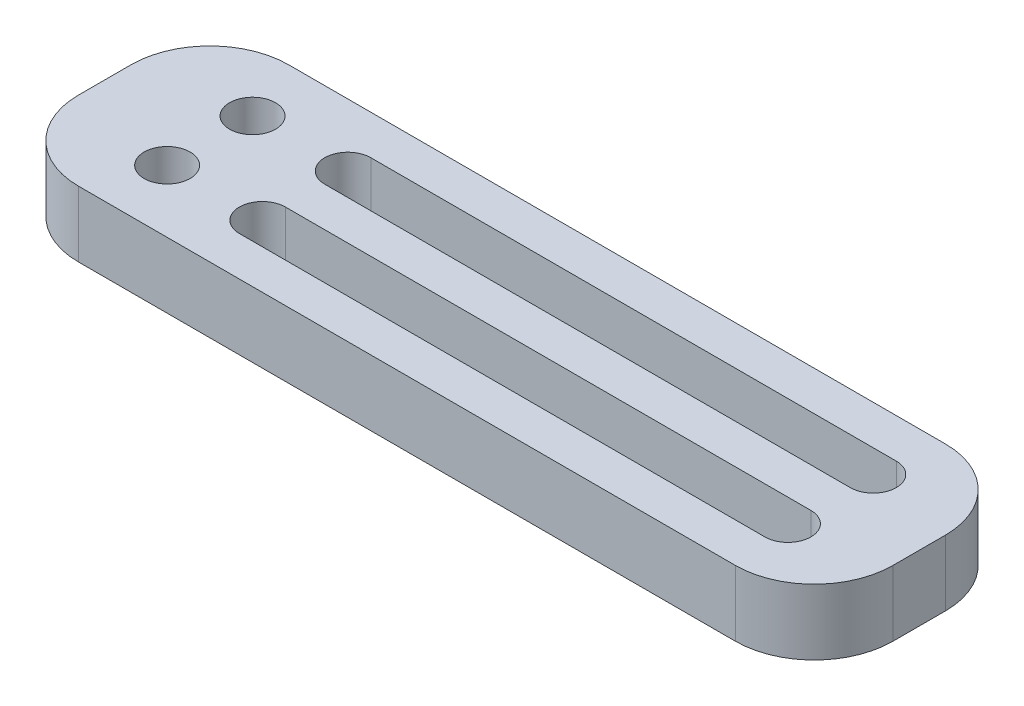
SolidWorks part; units mm, degrees
ref_plane "Front Plane" through (0, 0, 0) normal (0, 0, 1) x (1, 0, 0)
ref_plane "Top Plane" through (0, 0, 0) normal (0, 1, 0) x (1, 0, 0)
ref_plane "Right Plane" through (0, 0, 0) normal (1, 0, 0) x (0, 0, -1)
sketch "Sketch1" plane through (0, 0, 0) normal (0, 1, 0) x (1, 0, 0)
  line L0 (8, -10) -> (8, 6) construction
  line L1 (6, 6) -> (56, 6)
  line L2 (0, 0) -> (0, -4)
  line L3 (15.25, 1.25) -> (8, 1.25) construction
  line L4 (62, 0) -> (62, -4)
  line L5 (62, -2) -> (0, -2) construction
  line L6 (15.25, -5.25) -> (55.25, -5.25) construction
  line L7 (15.25, -7) -> (55.25, -7)
  line L8 (15.25, -3.5) -> (55.25, -3.5)
  line L9 (6, -10) -> (56, -10)
  line L11 (15.25, 1.25) -> (55.25, 1.25) construction
  line L12 (15.25, 3) -> (55.25, 3)
  line L13 (15.25, -0.5) -> (55.25, -0.5)
  circle A0 centre (8, 1.25) radius 1.75
  arc A1 (15.25, -7) -> (15.25, -3.5) centre (15.25, -5.25) cw
  arc A2 (62, -4) -> (56, -10) centre (56, -4) cw
  arc A3 (62, 0) -> (56, 6) centre (56, 0) ccw
  arc A4 (15.25, 3) -> (15.25, -0.5) centre (15.25, 1.25) ccw
  arc A5 (55.25, -0.5) -> (55.25, 3) centre (55.25, 1.25) ccw
  arc A6 (55.25, -3.5) -> (55.25, -7) centre (55.25, -5.25) cw
  arc A7 (6, 6) -> (0, 0) centre (6, 0) ccw
  circle A8 centre (8, -5.25) radius 1.75
  arc A9 (6, -10) -> (0, -4) centre (6, -4) cw
  point P13 (35.25, -5.25)
  point P19 (62, 6)
  point P22 (0, 0)
  point P23 (35.25, 1.25)
  point P31 (57, 1.25)
  point P37 (0, 0)
  dimension "D3" = 6.5
  dimension "D6" = 6
  dimension "D7" = 1.75
  dimension "D10" = 40
  dimension "D12" = 3
  dimension "D5" = 16
  dimension "D8" = 8
  dimension "D9" = 50
  dimension "D11" = 5
extrude "Boss-Extrude1" add sketch "Sketch1" against normal blind 5
